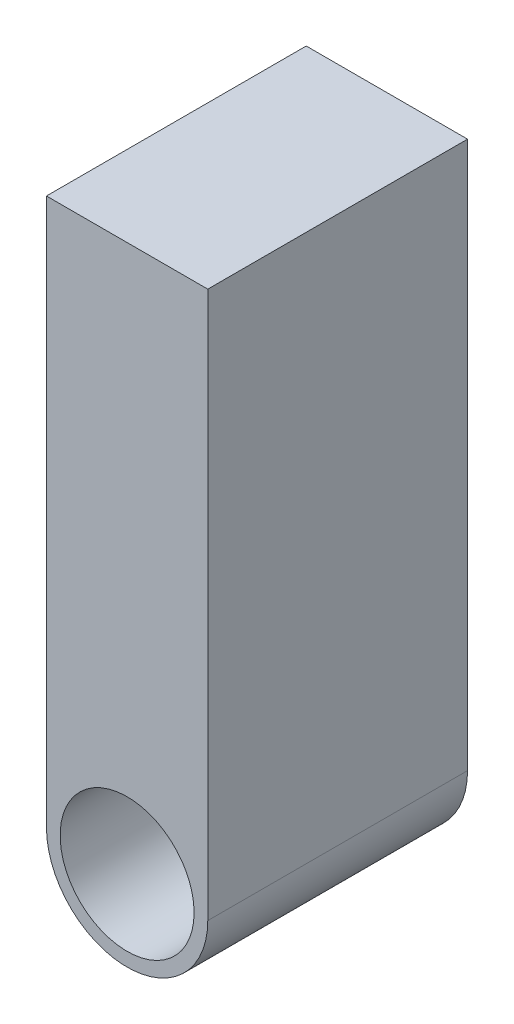
SolidWorks part; units mm, degrees
ref_plane "Front Plane" through (0, 0, 0) normal (0, 0, 1) x (1, 0, 0)
ref_plane "Top Plane" through (0, 0, 0) normal (0, 1, 0) x (1, 0, 0)
ref_plane "Right Plane" through (0, 0, 0) normal (1, 0, 0) x (0, 0, -1)
sketch "Sketch2" plane through (0, 0, 0) normal (0, 0, 1) x (1, 0, 0)
  line L0 (-14.986, 0) -> (-14.986, 101.6)
  line L1 (-14.986, 101.6) -> (14.986, 101.6)
  line L2 (14.986, 101.6) -> (14.986, 0)
  arc A2 (-14.986, 0) -> (14.986, 0) centre (0, 0) ccw
  dimension "D3" = 29.972
  dimension "D4" = 101.6
extrude "Boss-Extrude1" add sketch "Sketch2" along normal blind 48.26
sketch "Sketch3" plane through (0, 0, 48.26) normal (0, 0, 1) x (1, 0, 0)
  circle A0 centre (0, 0) radius 12.446
  dimension "D1" = 24.892
extrude "Cut-Extrude1" cut sketch "Sketch3" against normal blind 44.196
sketch "Sketch4" plane through (0, 0, 0) normal (0, 0, -1) x (-1, 0, 0)
  circle A0 centre (0, 0) radius 3.175
  dimension "D1" = 6.35
extrude "Cut-Extrude2" cut sketch "Sketch4" against normal blind 40.64
